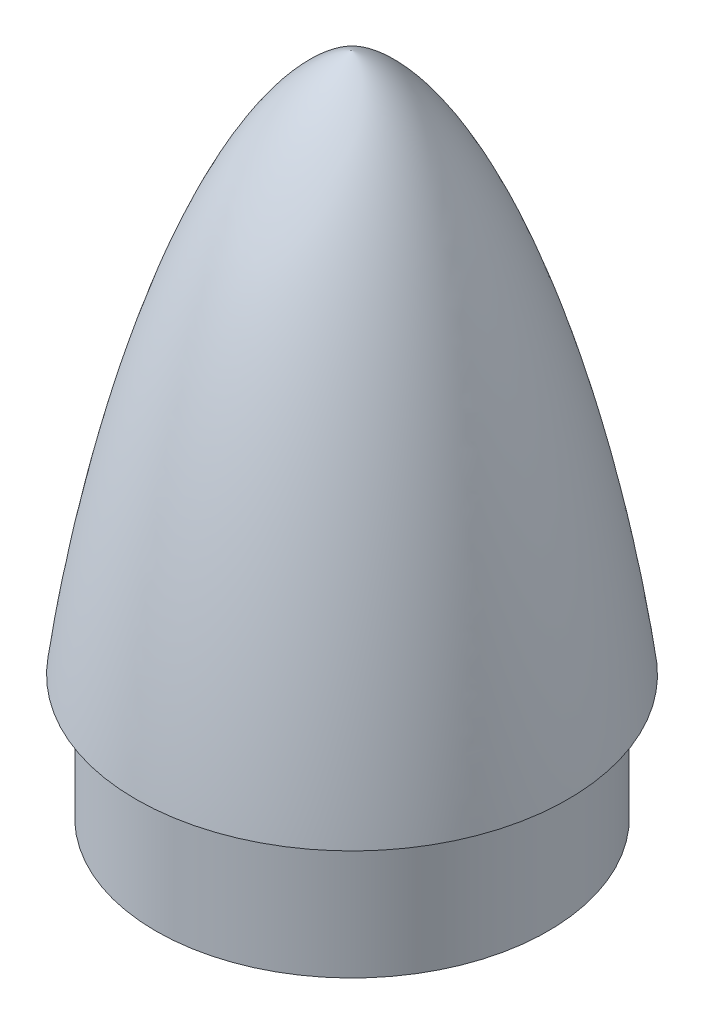
SolidWorks part; units mm, degrees
ref_plane "Front Plane" through (0, 0, 0) normal (0, 0, 1) x (1, 0, 0)
ref_plane "Top Plane" through (0, 0, 0) normal (0, 1, 0) x (1, 0, 0)
ref_plane "Right Plane" through (0, 0, 0) normal (1, 0, 0) x (0, 0, -1)
sketch "Sketch1" plane through (0, 0, 0) normal (1, 0, 0) x (0, 0, -1)
  line L1 (38.1, 663.719) -> (-38.1, 663.719) construction
  line L3 (-41.275, 663.719) -> (-40.275, 663.719)
  line L4 (0, 663.719) -> (0, 665.751)
  line L5 (-35.56, 663.719) -> (-29.21, 663.719)
  line L6 (-29.21, 663.719) -> (-29.21, 665.751)
  line L9 (-37.465, 663.719) -> (-37.465, 640)
  line L13 (0, 665.751) -> (-39.9874, 665.751)
  line L17 (-35.56, 663.719) -> (-35.56, 640)
  line L18 (-35.56, 663.719) -> (0, 663.719)
  line L19 (-41.275, 663.719) -> (-37.115, 696.1021) construction
  line L20 (-37.115, 696.1021) -> (-27.1863, 738.2754) construction
  line L21 (-27.1863, 738.2754) -> (-13.4752, 762.0097) construction
  line L22 (-13.4752, 762.0097) -> (0, 767) construction
  line L23 (0, 767) -> (0, 766)
  line L24 (-35.56, 640) -> (-37.465, 640)
  line L25 (-37.465, 663.719) -> (-40.275, 663.719)
  spline S0 degree 3 poles (-40.275, 663.719) (-36.7574, 688.9076) (-29.1141, 724.9978) (-11.2992, 760.035) (0, 766) knots 0 0 0 0 0.671213 1 1 1 1
  spline S2 degree 4 poles (-41.275, 663.719) (-37.115, 696.1021) (-27.1863, 738.2754) (-13.4752, 762.0097) (0, 767) knots 0 0 0 0 0 1 1 1 1 1
revolve "Revolve1" add sketch "Sketch1" angle 360 about L4
